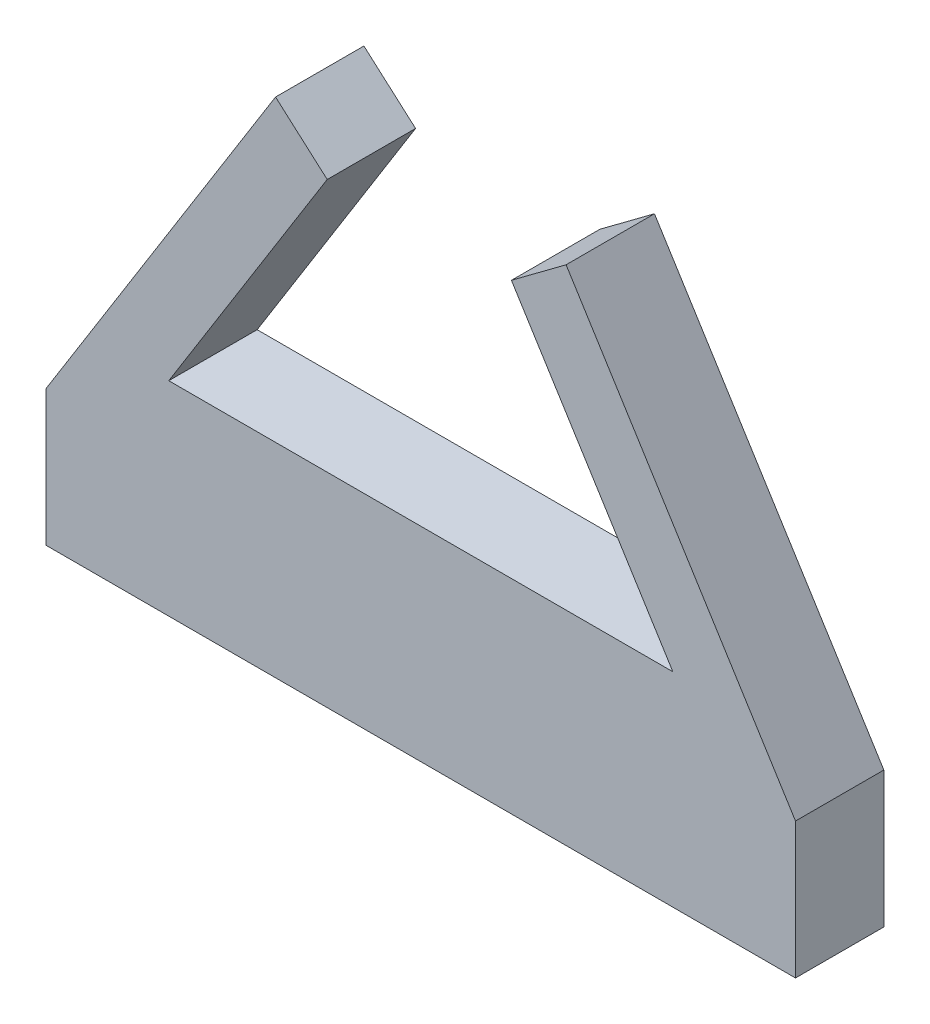
SolidWorks part; units mm, degrees
ref_plane "Front Plane" through (0, 0, 0) normal (0, 0, 1) x (1, 0, 0)
ref_plane "Top Plane" through (0, 0, 0) normal (0, 1, 0) x (1, 0, 0)
ref_plane "Right Plane" through (0, 0, 0) normal (1, 0, 0) x (0, 0, -1)
sketch "Sketch1" plane through (0, 0, 0) normal (0, 0, 1) x (1, 0, 0)
  line L0 (-5, -5) -> (-5, -2) construction
  line L1 (-5, 5) -> (5, 5) construction
  line L2 (-5, 5) -> (-5, -5) construction
  line L3 (-5, -5) -> (5, -5) construction
  line L4 (5, 5) -> (5, -5) construction
  line L5 (-5, 5) -> (5, -5) construction
  line L6 (-5, -5) -> (5, 5) construction
  line L7 (-2.5, 5) -> (2.5, 5) construction
  line L8 (-2.5, 5) -> (-2.5, -5) construction
  line L9 (-2.5, -5) -> (2.5, -5) construction
  line L10 (2.5, 5) -> (2.5, -5) construction
  line L11 (-2.5, 5) -> (2.5, -5) construction
  line L12 (-2.5, -5) -> (2.5, 5) construction
  line L13 (-2.5, 5) -> (2.5, 5) construction
  line L14 (-2.5, 5) -> (-2.5, 2) construction
  line L15 (-2.5, 2) -> (2.5, 2) construction
  line L16 (2.5, 5) -> (2.5, 2) construction
  line L17 (-2.5, 5) -> (2.5, 2) construction
  line L18 (-2.5, 2) -> (2.5, 5) construction
  line L19 (5, -5) -> (5, -2) construction
  line L20 (-5, -2) -> (-2.5, 2)
  line L21 (-2.5, 2) -> (-5, -2)
  line L22 (2.5, 2) -> (5, -2)
  line L23 (-5, -2) -> (-6.875, -5)
  line L24 (5, -2) -> (6.875, -5)
  line L25 (6.875, -5) -> (-6.875, -5)
  line L26 (-2.5, 2) -> (2.5, 2)
  line L27 (-2.5, 2.3) -> (2.6663, 2.3)
  line L28 (2.6663, 2.3) -> (5.2544, -1.841)
  line L29 (5.2544, -1.841) -> (7.4163, -5.3)
  line L30 (7.4163, -5.3) -> (-7.4163, -5.3)
  line L31 (-5.2544, -1.841) -> (-7.4163, -5.3)
  line L32 (-5.2544, -1.841) -> (-2.7544, 2.159)
  line L33 (-3.5584, -2.901) -> (-1.0584, 1.099)
  line L34 (-6.9504, -0.781) -> (-11.0248, -7.3)
  line L35 (11.0248, -7.3) -> (-11.0248, -7.3)
  line L36 (6.9504, -0.781) -> (11.0248, -7.3)
  line L37 (3.7748, 4.3) -> (6.9504, -0.781)
  line L38 (-2.5, 4.3) -> (3.7748, 4.3)
  line L39 (-6.9504, -0.781) -> (-4.2748, 3.5)
  line L40 (-4.2748, 3.5) -> (4.2748, 3.5)
  line L41 (4.2748, 3.5) -> (2.6663, 2.3)
  line L42 (-2.7544, 2.159) -> (-4.2748, 3.5)
  point P0 (0, 0)
  point P6 (0, 0)
  point P13 (0, 3.5)
  dimension "D1" = 10
  dimension "D2" = 10
  dimension "D3" = 5
  dimension "D4" = 3
  dimension "D5" = 3
  dimension "D6" = 3
  dimension "D7" = 0.3
  dimension "D8" = 2
extrude "Boss-Extrude1" add sketch "Sketch1" along normal blind 2.6 contours L32 L42 L39 L34 L35 L36 L37 L41 L28 L29 L30 L31
sketch "Sketch2" plane through (0, -7.3, 0) normal (0, -1, 0) x (1, 0, 0)
  line L1 (-11.0248, 2.6) -> (11.0248, 2.6)
  line L2 (-11.0248, 2.6) -> (-11.0248, 0)
  line L3 (-11.0248, 0) -> (11.0248, 0)
  line L4 (11.0248, 2.6) -> (11.0248, 0)
  line L5 (-11.0248, 2.6) -> (11.0248, 0) construction
  line L6 (-11.0248, 0) -> (11.0248, 2.6) construction
  point P4 (0, 1.3)
extrude "Boss-Extrude2" add sketch "Sketch2" along normal blind 4
